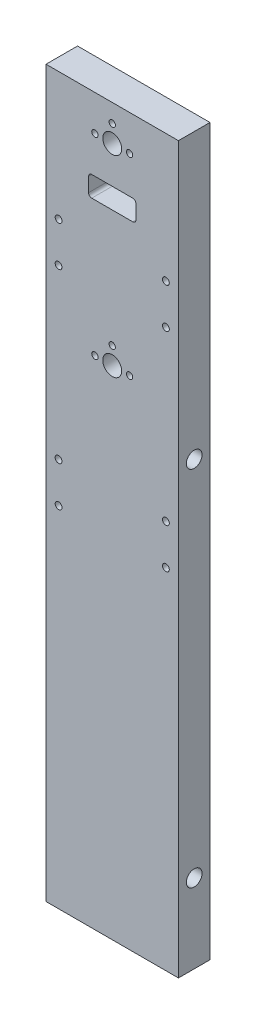
SolidWorks part; units mm, degrees
ref_plane "Front Plane" through (0, 0, 0) normal (0, 0, 1) x (1, 0, 0)
ref_plane "Top Plane" through (0, 0, 0) normal (0, 1, 0) x (1, 0, 0)
ref_plane "Right Plane" through (0, 0, 0) normal (1, 0, 0) x (0, 0, -1)
sketch "Sketch1" plane through (0, 0, 0) normal (0, 0, 1) x (1, 0, 0)
  line L0 (-18, -106) -> (18, -106) construction
  line L1 (42, 38.575) -> (42, -421.425)
  line L2 (-42, 38.575) -> (42, 38.575)
  line L3 (-42, 38.575) -> (-42, -421.425)
  line L6 (-18, 16) -> (18, 16) construction
  line L11 (-32.5, 38.575) -> (32.5, 38.575) construction
  line L14 (-42, -421.425) -> (42, -421.425)
  line L25 (-32.5, -371.425) -> (-32.5, 38.575) construction
  line L26 (-82.5, -421.425) -> (82.5, -421.425) construction
  line L27 (32.5, -371.425) -> (32.5, 38.575) construction
  line L28 (-32.5, -371.425) -> (32.5, -371.425) construction
  line L29 (82.5, -421.425) -> (82.5, 88.575) construction
  line L30 (-82.5, -421.425) -> (-82.5, 88.575) construction
  line L31 (-82.5, 88.575) -> (82.5, 88.575) construction
  circle A5 centre (0, -106) radius 6
  circle A6 centre (0, -106) radius 11 construction
  circle A7 centre (11, -106) radius 2
  circle A10 centre (0, -95) radius 2
  circle A12 centre (0, 16) radius 6
  circle A13 centre (11, 16) radius 2
  circle A14 centre (-11, -106) radius 2
  circle A15 centre (0, 27) radius 2
  circle A16 centre (-11, 16) radius 2
  circle A17 centre (0, 16) radius 11 construction
  dimension "D9" = 2
  dimension "D2" = 84
  dimension "D3" = 460
  dimension "D10" = 122
extrude "Boss-Extrude1" add sketch "Sketch1" along normal blind 20
sketch "Sketch2" plane through (0, 0, 0) normal (1, 0, 0) x (0, 0, -1)
  line L0 (-20, -371.425) -> (0, -371.425) construction
  line L1 (-20, -421.425) -> (0, -421.425) construction
  line L2 (-20, -141.425) -> (0, -141.425) construction
  line L3 (-20, -421.425) -> (-20, 38.575) construction
  line L4 (0, -421.425) -> (0, 38.575) construction
  circle A0 centre (-10, -141.425) radius 5
  circle A1 centre (-10, -371.425) radius 5
  point P2 (-10, -421.425)
  dimension "D1" = 280
  dimension "D2" = 230
extrude "Cut-Extrude1" cut sketch "Sketch2" against normal mid plane 100
sketch "Sketch3" plane through (0, 0, 0) normal (0, 0, 1) x (1, 0, 0)
  line L1 (-12.7, -67.117) -> (-41.656, -67.117)
  line L2 (41.656, -67.117) -> (12.7, -67.117)
  line L3 (-41.656, -22.9207) -> (-41.656, -67.117)
  line L4 (41.656, -22.9207) -> (41.656, -67.117)
  line L5 (12.7, -67.117) -> (12.7, -54.417)
  line L6 (34.036, -67.117) -> (34.036, -36.2127) construction
  line L7 (-12.7, -54.417) -> (-12.7, -67.117)
  line L8 (-34.036, -67.117) -> (-34.036, -36.2127) construction
  line L9 (39.497, -56.957) -> (28.575, -56.957) construction
  line L10 (30.734, -59.116) -> (37.338, -59.116)
  line L11 (37.338, -54.798) -> (30.734, -54.798)
  line L12 (-39.497, -31.557) -> (-28.575, -31.557) construction
  line L13 (30.734, -33.716) -> (37.338, -33.716)
  line L14 (-39.497, -56.957) -> (-28.575, -56.957) construction
  line L15 (39.497, -31.557) -> (28.575, -31.557) construction
  line L16 (37.338, -29.398) -> (30.734, -29.398)
  line L17 (-37.338, -29.398) -> (-30.734, -29.398)
  line L18 (-30.734, -33.716) -> (-37.338, -33.716)
  line L19 (-37.338, -54.798) -> (-30.734, -54.798)
  line L20 (-30.734, -59.116) -> (-37.338, -59.116)
  line L21 (30.988, -16.7615) -> (41.656, -22.9207)
  line L22 (30.988, -16.7615) -> (30.988, -11.999)
  line L23 (30.988, -11.999) -> (-30.988, -11.999)
  line L24 (-30.988, -11.999) -> (-30.988, -16.7615)
  line L25 (-30.988, -16.7615) -> (-41.656, -22.9207)
  line L26 (0, -11.999) -> (-19.4236, -11.999) construction
  line L27 (30.988, -16.7615) -> (-30.988, -16.7615) construction
  line L28 (0, 10) -> (-9.559, 10) construction
  arc A0 (37.338, -33.716) -> (37.338, -29.398) centre (37.338, -31.557) ccw
  arc A1 (30.734, -59.116) -> (30.734, -54.798) centre (30.734, -56.957) cw
  arc A2 (12.7, -54.417) -> (-12.7, -54.417) centre (0, -54.417) ccw
  arc A3 (37.338, -59.116) -> (37.338, -54.798) centre (37.338, -56.957) ccw
  arc A4 (-30.734, -33.716) -> (-30.734, -29.398) centre (-30.734, -31.557) ccw
  arc A5 (30.734, -33.716) -> (30.734, -29.398) centre (30.734, -31.557) cw
  arc A6 (-37.338, -59.116) -> (-37.338, -54.798) centre (-37.338, -56.957) cw
  arc A7 (-30.734, -59.116) -> (-30.734, -54.798) centre (-30.734, -56.957) ccw
  arc A8 (-37.338, -33.716) -> (-37.338, -29.398) centre (-37.338, -31.557) cw
  circle A9 centre (0, 16) radius 6 construction
  circle A12 centre (0, 16) radius 15 construction
  dimension "D1" = 68.072
  dimension "D2" = 83.312
  dimension "D3" = 12.7
sketch "Sketch4" plane through (0, 0, 0) normal (0, 0, 1) x (1, 0, 0)
  line L0 (0, -4.7625) -> (0, -30.7793) construction
  line L6 (34.036, -78.117) -> (34.036, -47.2127) construction
  line L8 (-34.036, -78.117) -> (-34.036, -47.2127) construction
  circle A2 centre (34.036, -42.557) radius 2.159
  circle A9 centre (34.036, -67.957) radius 2.159
  circle A10 centre (-34.036, -67.957) radius 2.159
  circle A11 centre (-34.036, -42.557) radius 2.159
  dimension "D1" = 68.072
extrude "Cut-Extrude2" cut sketch "Sketch4" along normal blind 20
sketch "Sketch5" plane through (0, 0, 0) normal (0, 0, 1) x (1, 0, 0)
  line L0 (15, -18.4995) -> (15, -9.4995)
  line L2 (-13, -20.4995) -> (13, -20.4995)
  line L4 (-15, -18.4995) -> (-15, -9.4995)
  line L5 (13, -7.4995) -> (-13, -7.4995)
  arc A0 (15, -9.4995) -> (13, -7.4995) centre (13, -9.4995) ccw
  arc A1 (-13, -7.4995) -> (-15, -9.4995) centre (-13, -9.4995) ccw
  arc A2 (-13, -20.4995) -> (-15, -18.4995) centre (-13, -18.4995) cw
  arc A3 (13, -20.4995) -> (15, -18.4995) centre (13, -18.4995) ccw
  dimension "D1" = 2
extrude "Cut-Extrude3" cut sketch "Sketch5" along normal blind 20
sketch "Sketch6" plane through (0, 0, 0) normal (0, 0, 1) x (1, 0, 0)
  line L6 (34.036, -210.118) -> (34.036, -179.2137) construction
  line L8 (-34.036, -210.118) -> (-34.036, -179.2137) construction
  line L28 (0, 10) -> (-9.559, 10) construction
  circle A2 centre (34.036, -174.558) radius 2.159
  circle A9 centre (-34.036, -174.558) radius 2.159
  circle A10 centre (-34.036, -199.958) radius 2.159
  circle A11 centre (34.036, -199.958) radius 2.159
  circle A12 centre (0, 16) radius 15 construction
extrude "Cut-Extrude4" cut sketch "Sketch6" along normal blind 20
